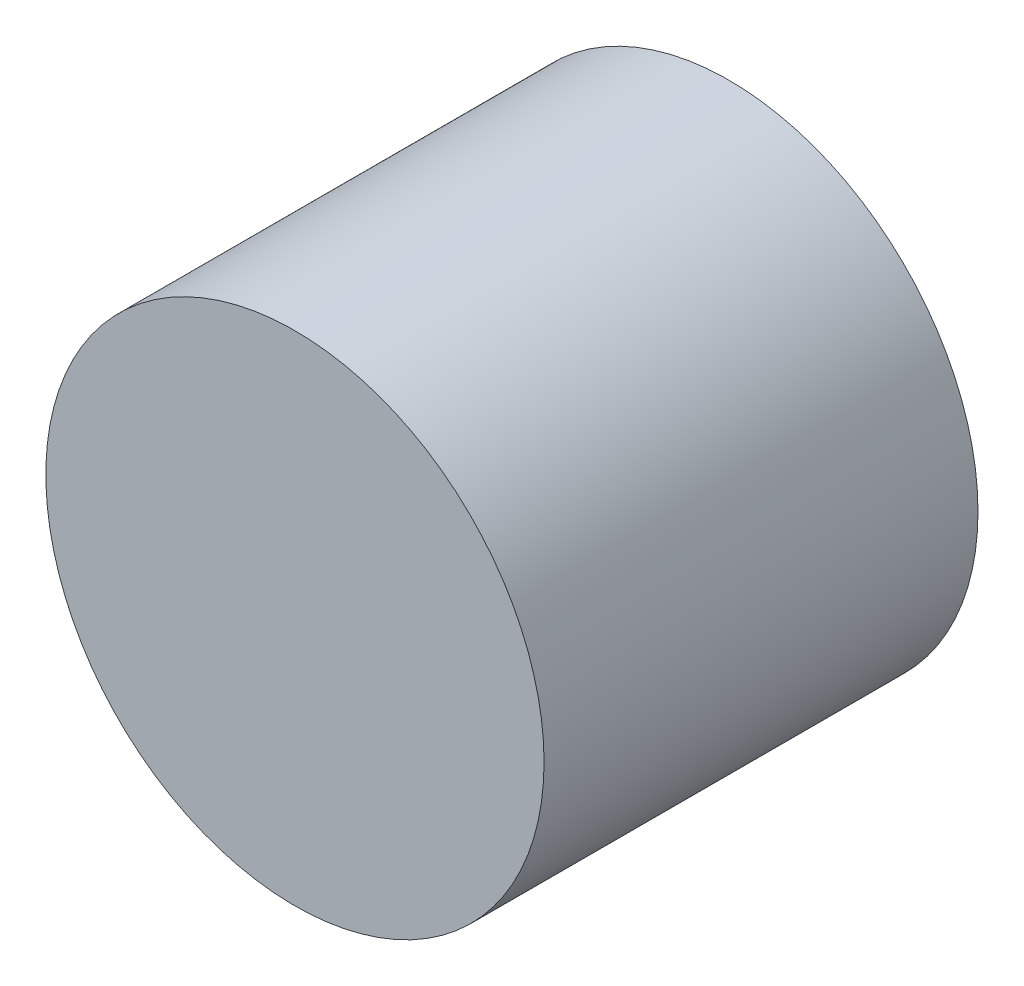
SolidWorks part; units mm, degrees
ref_plane "Piano frontale" through (0, 0, 0) normal (0, 0, 1) x (1, 0, 0)
ref_plane "Piano superiore" through (0, 0, 0) normal (0, 1, 0) x (1, 0, 0)
ref_plane "Piano destro" through (0, 0, 0) normal (1, 0, 0) x (0, 0, -1)
sketch "Schizzo1" plane through (0, 0, 0) normal (0, 0, 1) x (1, 0, 0)
  circle A0 centre (0, 0) radius 3.875
  dimension "D1" = 7.75
extrude "Estrusione-Estrusione1" add sketch "Schizzo1" along normal blind 6.75
